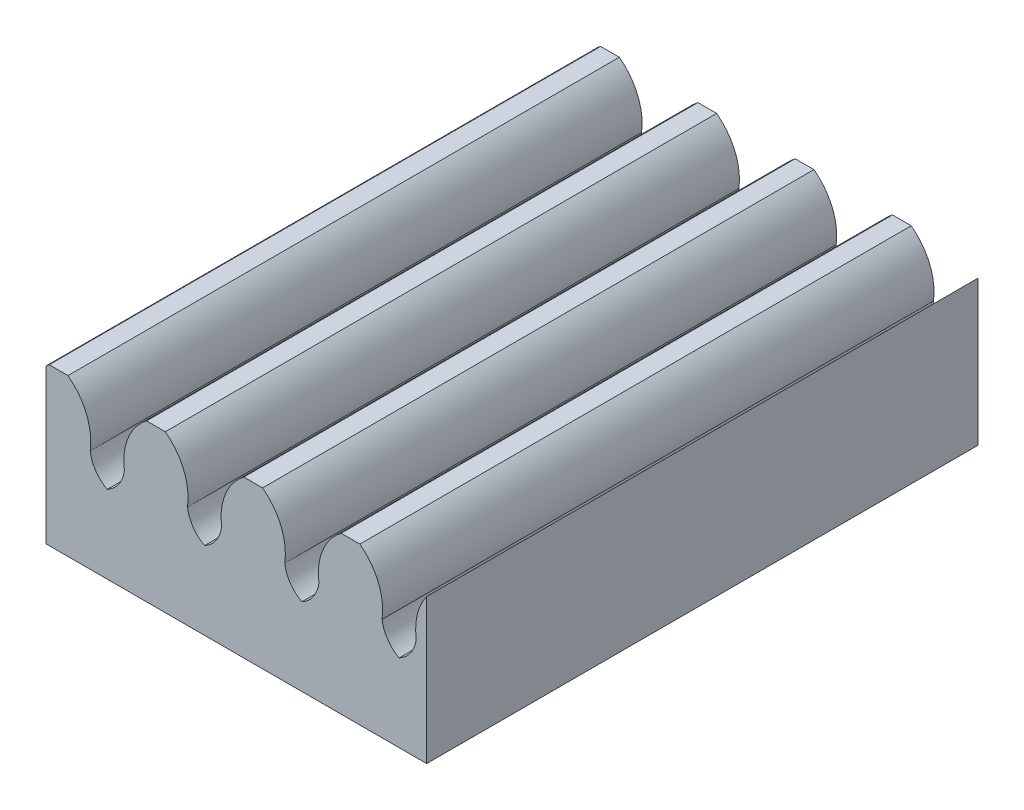
SolidWorks part; units mm, degrees
ref_plane "Front Plane" through (0, 0, 0) normal (0, 0, 1) x (1, 0, 0)
ref_plane "Top Plane" through (0, 0, 0) normal (0, 1, 0) x (1, 0, 0)
ref_plane "Right Plane" through (0, 0, 0) normal (1, 0, 0) x (0, 0, -1)
sketch "Sketch1" plane through (0, 0, 0) normal (0, 0, 1) x (1, 0, 0)
  line L1 (-14.215, 7) -> (-14.215, -0.2491)
  line L2 (-14.215, -0.2491) -> (0.9392, -0.2491)
  line L3 (0.9392, -0.2491) -> (3.3902, -0.2491)
  line L4 (3.3902, -0.2491) -> (3.3902, 7)
  line L6 (-14.215, 7) -> (3.3902, 7)
extrude "Boss-Extrude1" add sketch "Sketch1" along normal blind 25.5
sketch "Sketch2" plane through (0, 0, 0) normal (0, 0, 1) x (1, 0, 0)
  line L0 (-6.8813, 0.8955) -> (-6.8813, 9.6802) construction
  arc A5 (-6.8813, 3.3484) -> (-7.6713, 4.4984) centre (-6.1725, 4.6817) cw
  arc A12 (-7.6713, 4.4984) -> (-8.9813, 7.188) centre (-10.3038, 4.8801) ccw
  arc A13 (-6.0913, 4.4984) -> (-4.7813, 7.188) centre (-3.4588, 4.8801) cw
  arc A14 (-6.8813, 3.3484) -> (-6.0913, 4.4984) centre (-7.5901, 4.6817) ccw
  arc A15 (-8.9813, 7.188) -> (-4.7813, 7.188) centre (-6.8813, 3.6353) cw
  dimension "D4" = 2.66
  dimension "D5" = 1.51
  dimension "D6" = 1.15
  dimension "D8" = 2.1
  dimension "D10" = 0.79
extrude "Cut-Extrude1" cut sketch "Sketch2" along normal blind 26.12
pattern_linear "LPattern1" count 4 spacing 4.5 along (-1, 0, 0) count 9 spacing 4.5 along (1, 0, 0) of "Cut-Extrude1"
